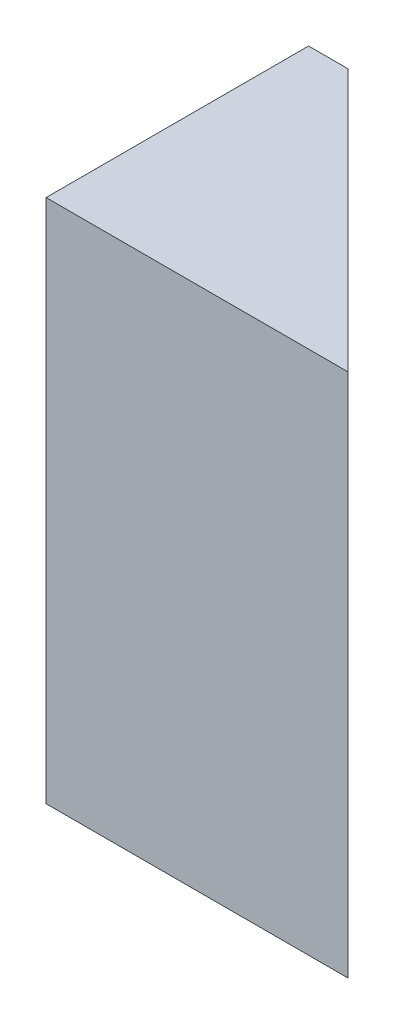
SolidWorks part; units mm, degrees
ref_plane "Спереди" through (0, 0, 0) normal (0, 0, 1) x (1, 0, 0)
ref_plane "Сверху" through (0, 0, 0) normal (0, 1, 0) x (1, 0, 0)
ref_plane "Справа" through (0, 0, 0) normal (1, 0, 0) x (0, 0, -1)
other "Configuration Table"
sketch "Эскиз1" plane through (0, 0, 0) normal (0, 1, 0) x (1, 0, 0)
  line L1 (0, 0) -> (40, 0)
  line L2 (0, 40) -> (40, 0)
  line L3 (0, 0) -> (-6, 0)
  line L4 (-6, 0) -> (-6, 40)
  line L5 (-6, 40) -> (0, 40)
  dimension "D1" = 6
  dimension "D2" = 40
  dimension "D3" = 40
extrude "Бобышка-Вытянуть1" add sketch "Эскиз1" along normal blind 80
